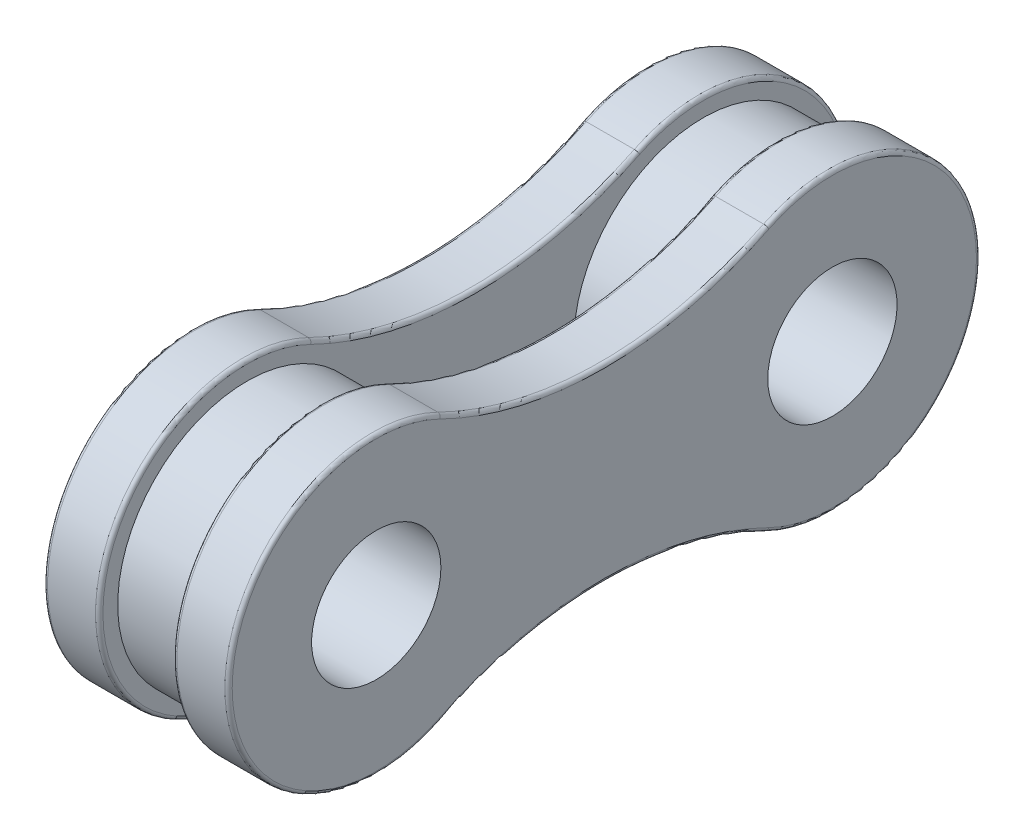
SolidWorks part; units mm, degrees
ref_plane "Front Plane" through (0, 0, 0) normal (0, 0, 1) x (1, 0, 0)
ref_plane "Top Plane" through (0, 0, 0) normal (0, 1, 0) x (1, 0, 0)
ref_plane "Right Plane" through (0, 0, 0) normal (1, 0, 0) x (0, 0, -1)
sketch "Sketch1" plane through (0, 0, 0) normal (1, 0, 0) x (0, 0, -1)
  line L0 (0, 0) -> (0, 3.6238) construction
  line L1 (-6.175, 0) -> (6.175, 0) construction
  circle A0 centre (-6.175, 0) radius 1.75
  arc A1 (-4.4107, 3.5899) -> (-4.4107, -3.5899) centre (-6.175, 0) ccw
  arc A2 (4.4107, 3.5899) -> (4.4107, -3.5899) centre (6.175, 0) cw
  circle A3 centre (6.175, 0) radius 1.75
  arc A4 (-4.4107, 3.5899) -> (4.4107, 3.5899) centre (0, 12.5646) ccw
  arc A5 (-4.4107, -3.5899) -> (4.4107, -3.5899) centre (0, -12.5646) cw
  dimension "D2" = 3.5
  dimension "D3" = 8
  dimension "D4" = 10
  dimension "D1" = 12.35
extrude "Boss-Extrude1" add sketch "Sketch1" along normal blind 1.5 from offset 1
sketch "Sketch2" plane through (0, 0, 0) normal (1, 0, 0) x (0, 0, -1)
  circle A0 centre (6.175, 0) radius 1.75 construction
  circle A1 centre (-6.175, 0) radius 1.75 construction
  circle A2 centre (6.175, 0) radius 1.75
  circle A3 centre (-6.175, 0) radius 1.75
  arc A4 (-4.4107, 3.5899) -> (4.4107, 3.5899) centre (0, 12.5646) ccw
  arc A5 (-4.4107, 3.5899) -> (-4.4107, -3.5899) centre (-6.175, 0) ccw
  arc A6 (4.4107, -3.5899) -> (-4.4107, -3.5899) centre (0, -12.5646) ccw
  arc A7 (4.4107, -3.5899) -> (4.4107, 3.5899) centre (6.175, 0) ccw
  arc A8 (-4.4107, 3.5899) -> (4.4107, 3.5899) centre (0, 12.5646) ccw
  arc A9 (-4.4107, 3.5899) -> (-4.4107, -3.5899) centre (-6.175, 0) ccw
  arc A10 (4.4107, -3.5899) -> (-4.4107, -3.5899) centre (0, -12.5646) ccw
  arc A11 (4.4107, -3.5899) -> (4.4107, 3.5899) centre (6.175, 0) ccw
  dimension "D1" = 0
extrude "Boss-Extrude2" add sketch "Sketch2" against normal blind 1.5 from offset 1 separate body offset against normal yes
sketch "Sketch3" plane through (0, 0, 0) normal (1, 0, 0) x (0, 0, -1)
  circle A0 centre (6.175, 0) radius 1.75 construction
  circle A1 centre (-6.175, 0) radius 1.75 construction
  circle A2 centre (6.175, 0) radius 1.75
  circle A3 centre (-6.175, 0) radius 1.75
  circle A4 centre (-6.175, 0) radius 3.5
  circle A5 centre (6.175, 0) radius 3.5
  dimension "D1" = 7
extrude "Boss-Extrude3" add sketch "Sketch3" along normal mid plane 2
fillet "Fillet1" radius 0.1 16 edges at (-2.5, 0, -10.175) (-2.5, -2.5646, 0) (-2.5, 0, 10.175) (-1, 0, -10.175) (-1, -2.5646, 0) (-1, 0, 10.175) (1, 0, -10.175) (1, -2.5646, 0) (1, 0, 10.175) (2.5, 0, -10.175) (2.5, -2.5646, 0) (2.5, 0, 10.175) (-2.5, 2.5646, 0) (-1, 2.5646, 0) (1, 2.5646, 0) (2.5, 2.5646, 0)
